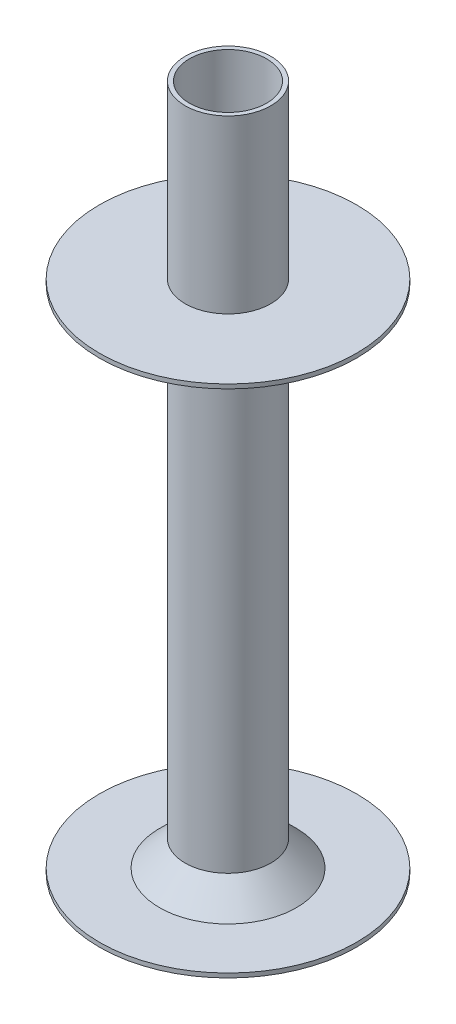
SolidWorks part; units mm, degrees
material "Brass"
ref_plane "前视基准面" through (0, 0, 0) normal (0, 0, 1) x (1, 0, 0)
ref_plane "上视基准面" through (0, 0, 0) normal (0, 1, 0) x (1, 0, 0)
ref_plane "右视基准面" through (0, 0, 0) normal (1, 0, 0) x (0, 0, -1)
sketch "Sketch1" plane through (0, 0, 0) normal (0, 1, 0) x (1, 0, 0)
  circle A0 centre (0, 0) radius 50
  dimension "D1" = 100
extrude "Boss-Extrude1" add sketch "Sketch1" along normal blind 800
sketch "Sketch2" plane through (0, 0, 0) normal (0, 0, 1) x (1, 0, 0)
  line L0 (-148.7389, 0) -> (160.6436, 0) construction
  line L1 (0, 0) -> (150, 0)
  line L2 (150, 0) -> (150, 5)
  line L3 (150, 5) -> (80, 5)
  line L4 (80, 5) -> (0, 85)
  line L5 (0, 85) -> (0, 0)
  line L6 (-148.7389, 600) -> (160.6436, 600) construction
  line L7 (0, -31.1699) -> (0, 834.8988) construction
  line L8 (0, 600) -> (150, 600)
  line L9 (150, 600) -> (150, 595)
  line L10 (150, 595) -> (80, 595)
  line L11 (80, 595) -> (0, 515)
  line L12 (0, 515) -> (0, 600)
  dimension "D1" = 150
  dimension "D2" = 70
  dimension "D3" = 45
  dimension "D4" = 5
  dimension "D6" = 150
  dimension "D7" = 5
  dimension "D8" = 70
  dimension "D9" = 45
  dimension "D5" = 600
revolve "Revolve1" add sketch "Sketch2" angle 360 about L7
sketch "Sketch3" plane through (0, 800, 0) normal (0, 1, 0) x (1, 0, 0)
  circle A0 centre (0, 0) radius 50 construction
  circle A1 centre (0, 0) radius 45
  dimension "D1" = 100
  dimension "D2" = 5
extrude "Cut-Extrude1" cut sketch "Sketch3" against normal through all
